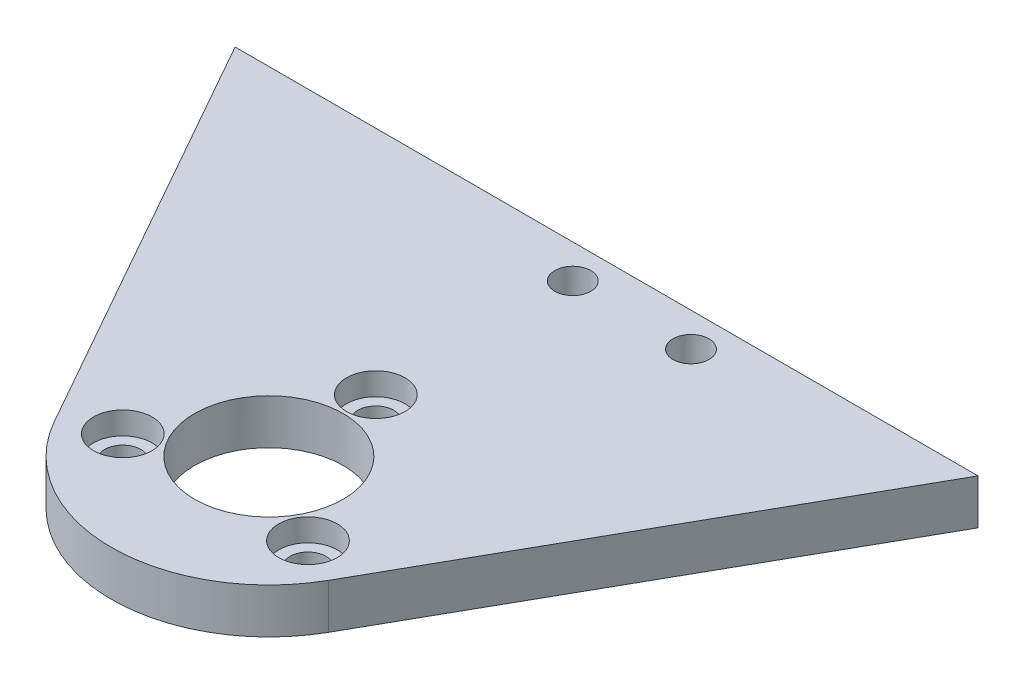
SolidWorks part; units mm, degrees
ref_plane "前视基准面" through (0, 0, 0) normal (0, 0, 1) x (1, 0, 0)
ref_plane "上视基准面" through (0, 0, 0) normal (0, 1, 0) x (1, 0, 0)
ref_plane "右视基准面" through (0, 0, 0) normal (1, 0, 0) x (0, 0, -1)
other "Configuration Table"
sketch "草图1" plane through (0, 0, 0) normal (0, 1, 0) x (1, 0, 0)
  line L5 (33, 30) -> (12.1933, -6.8793)
  line L7 (-12.1933, -6.8793) -> (-33, 30)
  line L8 (-33, 30) -> (33, 30)
  line L9 (0, 30) -> (0, 0) construction
  arc A0 (12.1933, -6.8793) -> (-12.1933, -6.8793) centre (0, 0) cw
  arc A1 (-12.1933, -6.8793) -> (12.1933, -6.8793) centre (0, 0) cw construction
  dimension "D1" = 66
  dimension "D2" = 14
  dimension "D3" = 30
extrude "凸台-拉伸1" add sketch "草图1" along normal blind 4
sketch "草图3" plane through (0, 4, 0) normal (0, 1, 0) x (1, 0, 0)
  line L3 (12.1933, -6.8793) -> (33, 30)
  line L4 (33, 30) -> (-33, 30)
  line L5 (-33, 30) -> (-12.1933, -6.8793)
  line L6 (12.1933, -6.8793) -> (33, 30) construction
  line L7 (33, 30) -> (-33, 30) construction
  line L8 (-33, 30) -> (-12.1933, -6.8793) construction
  circle A0 centre (-8.2272, -4.75) radius 1.6
  arc A1 (-12.1933, -6.8793) -> (12.1933, -6.8793) centre (0, 0) ccw
  arc A2 (-12.1933, -6.8793) -> (12.1933, -6.8793) centre (0, 0) ccw construction
  circle A3 centre (0, 9.5) radius 1.6
  circle A4 centre (8.2272, -4.75) radius 1.6
  circle A5 centre (0, 0) radius 6.6
  point P13 (0, 0)
  dimension "D2" = 3.2
  dimension "D4" = 3
  dimension "D5" = 13.2
  dimension "D3" = 9.5
  dimension "D1" = 0
extrude "切除-拉伸3" cut sketch "草图3" against normal up to surface (4 mm away) contours A0 | A4 | A5 | A3 up to face at (0, 0, -9.7802)
sketch "草图4" plane through (0, 4, 0) normal (0, 1, 0) x (1, 0, 0)
  line L0 (0, 30) -> (0, 27) construction
  line L1 (0, 27) -> (10.5, 27)
  line L2 (0, 0) -> (0, 27) construction
  line L4 (12.1933, -6.8793) -> (33, 30)
  line L5 (33, 30) -> (-33, 30)
  line L6 (-33, 30) -> (-12.1933, -6.8793)
  line L7 (12.1933, -6.8793) -> (33, 30) construction
  line L8 (33, 30) -> (-33, 30) construction
  line L9 (-33, 30) -> (-12.1933, -6.8793) construction
  circle A0 centre (0, 27) radius 1.6
  circle A1 centre (10.5, 27) radius 1.6
  arc A3 (-12.1933, -6.8793) -> (12.1933, -6.8793) centre (0, 0) ccw
  arc A4 (-12.1933, -6.8793) -> (12.1933, -6.8793) centre (0, 0) ccw construction
  dimension "D1" = 3.2
  dimension "D2" = 3.2
  dimension "D3" = 10.5
  dimension "D4" = 0
  dimension "D5" = 3
extrude "切除-拉伸4" cut sketch "草图4" against normal up to surface (4 mm away) contours A0 | A1 up to face at (-8.2272, 0, 3.15)
sketch "草图5" plane through (0, 4, 0) normal (0, 1, 0) x (1, 0, 0)
  circle A0 centre (8.2272, -4.75) radius 1.6 construction
  circle A1 centre (-8.2272, -4.75) radius 1.6 construction
  circle A2 centre (0, 0) radius 6.6 construction
  circle A3 centre (0, 9.5) radius 1.6 construction
  circle A8 centre (8.2272, -4.75) radius 1.6 construction
  circle A9 centre (-8.2272, -4.75) radius 1.6 construction
  circle A10 centre (0, 0) radius 6.6 construction
  circle A11 centre (0, 9.5) radius 1.6 construction
  circle A12 centre (0, 9.5) radius 2.6
  circle A13 centre (8.2272, -4.75) radius 2.6
  circle A14 centre (-8.2272, -4.75) radius 2.6
  dimension "D1" = 5.2
  dimension "D2" = 5.2
  dimension "D3" = 5.2
  dimension "D5" = 13.2
  dimension "D4" = 9.5
extrude "切除-拉伸6" cut sketch "草图5" against normal blind 2
